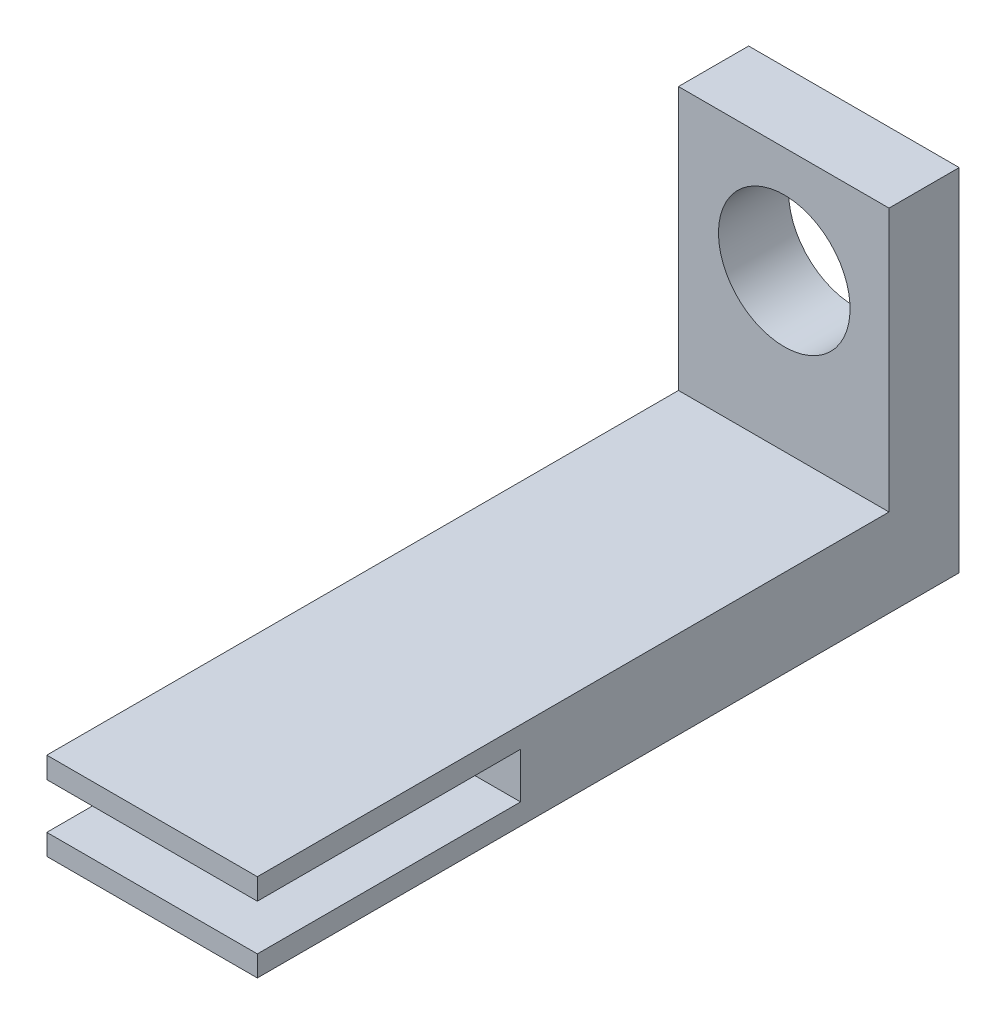
SolidWorks part; units mm, degrees
ref_plane "Front Plane" through (0, 0, 0) normal (0, 0, 1) x (1, 0, 0)
ref_plane "Top Plane" through (0, 0, 0) normal (0, 1, 0) x (1, 0, 0)
ref_plane "Right Plane" through (0, 0, 0) normal (1, 0, 0) x (0, 0, -1)
sketch "Sketch2" plane through (0, 0, 0) normal (0, 1, 0) x (1, 0, 0)
  line L1 (-15.7647, 43.0588) -> (-3.7647, 43.0588)
  line L2 (-15.7647, 43.0588) -> (-15.7647, 3.0588)
  line L3 (-15.7647, 3.0588) -> (-3.7647, 3.0588)
  line L4 (-3.7647, 43.0588) -> (-3.7647, 3.0588)
  line L5 (-15.7647, 43.0588) -> (-3.7647, 3.0588) construction
  line L6 (-15.7647, 3.0588) -> (-3.7647, 43.0588) construction
  point P0 (-9.7647, 23.0588)
  dimension "D1" = 40
  dimension "D2" = 12
extrude "Boss-Extrude1" add sketch "Sketch2" along normal blind 5
sketch "Sketch3" plane through (0, 0, -3.0588) normal (0, 0, 1) x (1, 0, 0)
  line L0 (-3.7647, 5) -> (-3.7647, 0) construction
  line L1 (-15.7688, 1.1896) -> (-3.7647, 1.1896)
  line L2 (-15.7688, 1.1896) -> (-15.7688, 3.7896)
  line L3 (-15.7688, 3.7896) -> (-3.7647, 3.7896)
  line L4 (-3.7647, 1.1896) -> (-3.7647, 3.7896)
  line L5 (-15.7688, 1.1896) -> (-3.7647, 3.7896) construction
  line L6 (-15.7688, 3.7896) -> (-3.7647, 1.1896) construction
  point P0 (-9.7668, 2.4896)
  dimension "D1" = 2.6
extrude "Cut-Extrude1" cut sketch "Sketch3" against normal blind 15
sketch "Sketch4" plane through (0, 5, 0) normal (0, 1, 0) x (1, 0, 0)
  line L0 (-3.7647, 3.0588) -> (-3.7647, 43.0588) construction
  line L1 (-15.7647, 43.0588) -> (-3.7647, 43.0588)
  line L2 (-15.7647, 43.0588) -> (-15.7647, 39.0588)
  line L3 (-15.7647, 39.0588) -> (-3.7647, 39.0588)
  line L4 (-3.7647, 43.0588) -> (-3.7647, 39.0588)
  dimension "D1" = 4
extrude "Boss-Extrude2" add sketch "Sketch4" along normal blind 15
sketch "Sketch5" plane through (0, 0, -43.0588) normal (0, 0, -1) x (-1, 0, 0)
  circle A0 centre (9.7348, 13.9179) radius 3.75
  dimension "D1" = 7.5
extrude "Cut-Extrude2" cut sketch "Sketch5" against normal blind 15
